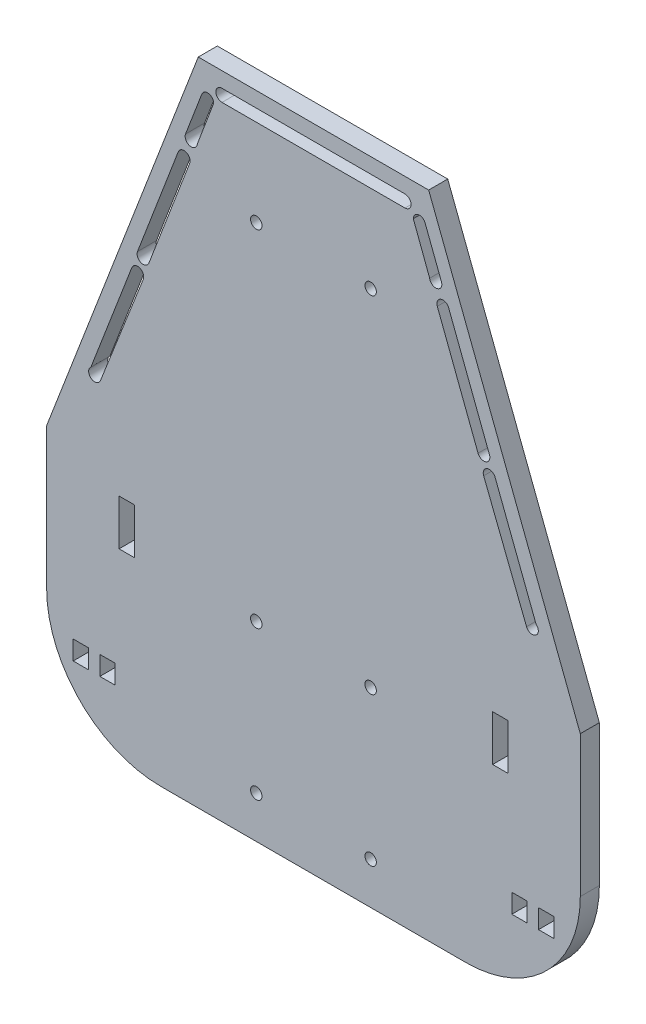
SolidWorks part; units mm, degrees
ref_plane "Front Plane" through (0, 0, 0) normal (0, 0, 1) x (1, 0, 0)
ref_plane "Top Plane" through (0, 0, 0) normal (0, 1, 0) x (1, 0, 0)
ref_plane "Right Plane" through (0, 0, 0) normal (1, 0, 0) x (0, 0, -1)
sketch "Sketch2" plane through (0, 0, 0) normal (0, 0, 1) x (1, 0, 0)
  line L0 (0, 0) -> (40, 0)
  line L1 (0, 0) -> (-40, 0)
  line L2 (-70, 30) -> (-70, 67)
  line L3 (70, 30) -> (70, 67)
  line L4 (-70, 67) -> (-30.2212, 170.6274)
  line L7 (70, 67) -> (30.2212, 170.6274)
  line L12 (-30.2212, 170.6274) -> (30.2212, 170.6274)
  arc A0 (-40, 0) -> (-70, 30) centre (-40, 30) cw
  arc A1 (40, 0) -> (70, 30) centre (40, 30) ccw
  dimension "D1" = 30
  dimension "D2" = 30
  dimension "D3" = 60.4423
  dimension "D5" = 37
  dimension "D6" = 70
  dimension "D7" = 70
  dimension "D8" = 159
  dimension "D9" = 159
  dimension "D10" = 111
  dimension "D11" = 111
  dimension "D12" = 37
extrude "Boss-Extrude2" add sketch "Sketch2" along normal blind 1
sketch "Sketch41" plane through (0, 0, 1) normal (0, 0, 1) x (1, 0, 0)
  line L0 (-33.5636, 151.4672) -> (-29.2832, 162.6778)
  line L1 (-32.4778, 145.3397) -> (-43.1788, 117.3131)
  line L2 (24, 166.6274) -> (-24, 166.6274)
  line L3 (-24, 163.4274) -> (24, 163.4274)
  line L4 (-26.1885, 162.1071) -> (-30.4778, 150.7272)
  line L9 (-35.4674, 146.4812) -> (-46.1683, 118.4546)
  line L10 (33.5636, 151.4672) -> (29.2832, 162.6778)
  line L11 (-55.8956, 84.2573) -> (-44.6465, 112.9189)
  line L12 (26.1885, 162.1071) -> (30.4778, 150.7272)
  line L13 (-47.6397, 114.0937) -> (-58.3908, 86.0863)
  line L14 (35.4674, 146.4812) -> (46.1683, 118.4546)
  line L15 (32.4778, 145.3397) -> (43.1788, 117.3131)
  line L16 (55.8956, 84.2573) -> (44.6465, 112.9189)
  line L17 (47.6397, 114.0937) -> (58.3908, 86.0863)
  line L18 (0, 0) -> (-11, 0)
  line L19 (51, 48.5) -> (47, 48.5)
  line L20 (-40, 0) -> (40, 0) construction
  line L21 (51, 60.5) -> (47, 60.5)
  line L22 (-63.037, 17) -> (-59.037, 17)
  line L23 (-63.037, 17) -> (-63.037, 22)
  line L24 (-63.037, 22) -> (-59.037, 22)
  line L25 (-59.037, 17) -> (-59.037, 22)
  line L26 (47, 48.5) -> (47, 60.5)
  line L27 (-56.037, 17) -> (-52.037, 17)
  line L28 (-56.037, 17) -> (-56.037, 22)
  line L29 (-56.037, 22) -> (-52.037, 22)
  line L30 (-52.037, 17) -> (-52.037, 22)
  line L31 (-51, 48.5) -> (-47, 48.5)
  line L32 (-51, 48.5) -> (-51, 60.5)
  line L33 (-51, 60.5) -> (-47, 60.5)
  line L34 (-47, 48.5) -> (-47, 60.5)
  line L35 (51, 48.5) -> (51, 60.5)
  line L36 (56.037, 17) -> (52.037, 17)
  line L37 (52.037, 17) -> (52.037, 22)
  line L38 (56.037, 17) -> (56.037, 22)
  line L39 (56.037, 22) -> (52.037, 22)
  line L40 (63.037, 17) -> (59.037, 17)
  line L41 (59.037, 17) -> (59.037, 22)
  line L42 (63.037, 22) -> (59.037, 22)
  line L43 (63.037, 17) -> (63.037, 22)
  arc A0 (-24, 166.6274) -> (-24, 163.4274) centre (-24, 165.0274) ccw
  arc A1 (24, 166.6274) -> (24, 163.4274) centre (24, 165.0274) cw
  arc A2 (-29.2832, 162.6778) -> (-26.1885, 162.1071) centre (-27.7885, 162.1071) cw
  arc A3 (-33.5636, 151.4672) -> (-30.4778, 150.7272) centre (-32.0689, 150.8964) ccw
  arc A4 (-35.4674, 146.4812) -> (-32.4778, 145.3397) centre (-33.9726, 145.9104) cw
  arc A5 (-43.1788, 117.3131) -> (-46.1683, 118.4546) centre (-44.6736, 117.8839) cw
  arc A6 (-44.6465, 112.9189) -> (-47.6397, 114.0937) centre (-46.1431, 113.5063) ccw
  arc A7 (-55.8956, 84.2573) -> (-58.3908, 86.0863) centre (-57.385, 84.8419) cw
  arc A8 (29.2832, 162.6778) -> (26.1885, 162.1071) centre (27.7885, 162.1071) ccw
  arc A9 (33.5636, 151.4672) -> (30.4778, 150.7272) centre (32.0689, 150.8964) cw
  arc A10 (35.4674, 146.4812) -> (32.4778, 145.3397) centre (33.9726, 145.9104) ccw
  arc A11 (43.1788, 117.3131) -> (46.1683, 118.4546) centre (44.6736, 117.8839) ccw
  arc A12 (44.6465, 112.9189) -> (47.6397, 114.0937) centre (46.1431, 113.5063) cw
  arc A13 (55.8956, 84.2573) -> (58.3908, 86.0863) centre (57.385, 84.8419) ccw
  circle A14 centre (-15, 140.6274) radius 1.5
  circle A15 centre (-15, 15) radius 1.5
  circle A16 centre (-15, 65) radius 1.5
  circle A17 centre (15, 140.6274) radius 1.5
  circle A18 centre (15, 65) radius 1.5
  circle A19 centre (15, 15) radius 1.5
  point P8 (0, 166.6274)
extrude "Cut-Extrude42" cut sketch "Sketch41" against normal blind 19 contours L38 L39 L37 L36 | L27 L30 L29 L28 | A16 | A18 | A7 L11 A6 L13 | A5 L1 A4 L9 | A1 L2 A0 L3 | A9 L10 A8 L12 | L16 A13 L17 A12 | A14 | A17 | L26 L21 L35 L19 | L32 L33 L34 L31 | L41 L42 L43 L40 | A19 | A15 | L24 L25 L22 L23 | L0 A2 L4 A3 | L14 A11 L15 A10
sketch "Sketch42" plane through (0, 0, 1) normal (0, 0, 1) x (1, 0, 0)
  line L6 (-40, 0) -> (40, 0)
  line L7 (70, 30) -> (70, 67)
  line L8 (70, 67) -> (30.2212, 170.6274)
  line L9 (30.2212, 170.6274) -> (-30.2212, 170.6274)
  line L10 (-30.2212, 170.6274) -> (-70, 67)
  line L11 (-70, 67) -> (-70, 30)
  line L12 (-40, 0) -> (40, 0)
  line L13 (70, 30) -> (70, 67)
  line L14 (70, 67) -> (30.2212, 170.6274)
  line L15 (30.2212, 170.6274) -> (-30.2212, 170.6274)
  line L16 (-30.2212, 170.6274) -> (-70, 67)
  line L17 (-70, 67) -> (-70, 30)
  arc A2 (40, 0) -> (70, 30) centre (40, 30) ccw
  arc A3 (-70, 30) -> (-40, 0) centre (-40, 30) ccw
  arc A4 (40, 0) -> (70, 30) centre (40, 30) ccw
  arc A5 (-70, 30) -> (-40, 0) centre (-40, 30) ccw
  dimension "D1" = 0
extrude "Boss-Extrude17" add sketch "Sketch42" along normal blind 4
sketch "Sketch45" plane through (0, 0, 5) normal (0, 0, 1) x (1, 0, 0)
sketch "Sketch47" plane through (0, 0, 0) normal (0, 0, -1) x (-1, 0, 0)
  line L0 (63.037, 17) -> (63.037, 22) construction
  line L1 (63.037, 22) -> (59.037, 22) construction
  line L2 (59.037, 22) -> (59.037, 17) construction
  line L3 (59.037, 17) -> (63.037, 17) construction
  line L4 (52.037, 22) -> (52.037, 17) construction
  line L5 (52.037, 17) -> (56.037, 17) construction
  line L6 (56.037, 17) -> (56.037, 22) construction
  line L7 (56.037, 22) -> (52.037, 22) construction
  line L8 (-52.037, 22) -> (-56.037, 22) construction
  line L9 (-56.037, 22) -> (-56.037, 17) construction
  line L10 (-56.037, 17) -> (-52.037, 17) construction
  line L11 (-52.037, 17) -> (-52.037, 22) construction
  line L12 (-63.037, 17) -> (-59.037, 17) construction
  line L13 (-59.037, 17) -> (-59.037, 22) construction
  line L14 (-59.037, 22) -> (-63.037, 22) construction
  line L15 (-63.037, 22) -> (-63.037, 17) construction
  line L16 (-51, 48.5) -> (-47, 48.5) construction
  line L17 (-47, 48.5) -> (-47, 60.5) construction
  line L18 (-47, 60.5) -> (-51, 60.5) construction
  line L19 (-51, 60.5) -> (-51, 48.5) construction
  line L20 (47, 60.5) -> (47, 48.5) construction
  line L21 (47, 48.5) -> (51, 48.5) construction
  line L22 (51, 48.5) -> (51, 60.5) construction
  line L23 (51, 60.5) -> (47, 60.5) construction
  line L24 (63.037, 17) -> (63.037, 22)
  line L25 (63.037, 22) -> (59.037, 22)
  line L26 (59.037, 22) -> (59.037, 17)
  line L27 (59.037, 17) -> (63.037, 17)
  line L28 (52.037, 22) -> (52.037, 17)
  line L29 (52.037, 17) -> (56.037, 17)
  line L30 (56.037, 17) -> (56.037, 22)
  line L31 (56.037, 22) -> (52.037, 22)
  line L32 (-52.037, 22) -> (-56.037, 22)
  line L33 (-56.037, 22) -> (-56.037, 17)
  line L34 (-56.037, 17) -> (-52.037, 17)
  line L35 (-52.037, 17) -> (-52.037, 22)
  line L36 (-63.037, 17) -> (-59.037, 17)
  line L37 (-59.037, 17) -> (-59.037, 22)
  line L38 (-59.037, 22) -> (-63.037, 22)
  line L39 (-63.037, 22) -> (-63.037, 17)
  line L40 (-51, 48.5) -> (-47, 48.5)
  line L41 (-47, 48.5) -> (-47, 60.5)
  line L42 (-47, 60.5) -> (-51, 60.5)
  line L43 (-51, 60.5) -> (-51, 48.5)
  line L44 (47, 60.5) -> (47, 48.5)
  line L45 (47, 48.5) -> (51, 48.5)
  line L46 (51, 48.5) -> (51, 60.5)
  line L47 (51, 60.5) -> (47, 60.5)
extrude "Cut-Extrude47" cut sketch "Sketch47" against normal through all
sketch "Sketch48" plane through (0, 0, 0) normal (0, 0, -1) x (-1, 0, 0)
  line L0 (-43.1788, 117.3131) -> (-32.4778, 145.3397) construction
  line L1 (-35.4674, 146.4812) -> (-46.1683, 118.4546) construction
  line L2 (-55.8956, 84.2573) -> (-44.6465, 112.9189) construction
  line L3 (-47.6397, 114.0937) -> (-58.3908, 86.0863) construction
  line L4 (-30.4778, 150.7272) -> (-26.1885, 162.1071) construction
  line L5 (-29.2832, 162.6778) -> (-33.5636, 151.4672) construction
  line L6 (-24, 163.4274) -> (24, 163.4274) construction
  line L7 (24, 166.6274) -> (-24, 166.6274) construction
  line L8 (26.1885, 162.1071) -> (30.4778, 150.7272) construction
  line L9 (33.5636, 151.4672) -> (29.2832, 162.6778) construction
  line L10 (46.1683, 118.4546) -> (35.4674, 146.4812) construction
  line L11 (32.4778, 145.3397) -> (43.1788, 117.3131) construction
  line L12 (58.3908, 86.0863) -> (47.6397, 114.0937) construction
  line L13 (44.6465, 112.9189) -> (55.8956, 84.2573) construction
  line L14 (-43.1788, 117.3131) -> (-32.4778, 145.3397)
  line L15 (-35.4674, 146.4812) -> (-46.1683, 118.4546)
  line L16 (-55.8956, 84.2573) -> (-44.6465, 112.9189)
  line L17 (-47.6397, 114.0937) -> (-58.3908, 86.0863)
  line L18 (-30.4778, 150.7272) -> (-26.1885, 162.1071)
  line L19 (-29.2832, 162.6778) -> (-33.5636, 151.4672)
  line L20 (-24, 163.4274) -> (24, 163.4274)
  line L21 (24, 166.6274) -> (-24, 166.6274)
  line L22 (26.1885, 162.1071) -> (30.4778, 150.7272)
  line L23 (33.5636, 151.4672) -> (29.2832, 162.6778)
  line L24 (46.1683, 118.4546) -> (35.4674, 146.4812)
  line L25 (32.4778, 145.3397) -> (43.1788, 117.3131)
  line L26 (58.3908, 86.0863) -> (47.6397, 114.0937)
  line L27 (44.6465, 112.9189) -> (55.8956, 84.2573)
  arc A0 (-32.4778, 145.3397) -> (-35.4674, 146.4812) centre (-33.9726, 145.9104) ccw construction
  arc A1 (-46.1683, 118.4546) -> (-43.1788, 117.3131) centre (-44.6736, 117.8839) ccw construction
  arc A2 (-44.6465, 112.9189) -> (-47.6397, 114.0937) centre (-46.1431, 113.5063) ccw construction
  arc A3 (-58.3908, 86.0863) -> (-55.8956, 84.2573) centre (-57.385, 84.8419) ccw construction
  arc A4 (-33.5636, 151.4672) -> (-30.4778, 150.7272) centre (-32.0689, 150.8964) ccw construction
  arc A5 (-26.1885, 162.1071) -> (-29.2832, 162.6778) centre (-27.7885, 162.1071) ccw construction
  arc A6 (-24, 166.6274) -> (-24, 163.4274) centre (-24, 165.0274) ccw construction
  arc A7 (24, 163.4274) -> (24, 166.6274) centre (24, 165.0274) ccw construction
  circle A8 centre (-15, 140.6274) radius 1.5 construction
  circle A9 centre (15, 140.6274) radius 1.5 construction
  arc A10 (30.4778, 150.7272) -> (33.5636, 151.4672) centre (32.0689, 150.8964) ccw construction
  arc A11 (29.2832, 162.6778) -> (26.1885, 162.1071) centre (27.7885, 162.1071) ccw construction
  arc A12 (43.1788, 117.3131) -> (46.1683, 118.4546) centre (44.6736, 117.8839) ccw construction
  arc A13 (35.4674, 146.4812) -> (32.4778, 145.3397) centre (33.9726, 145.9104) ccw construction
  arc A14 (55.8956, 84.2573) -> (58.3908, 86.0863) centre (57.385, 84.8419) ccw construction
  arc A15 (47.6397, 114.0937) -> (44.6465, 112.9189) centre (46.1431, 113.5063) ccw construction
  arc A16 (-32.4778, 145.3397) -> (-35.4674, 146.4812) centre (-33.9726, 145.9104) ccw
  arc A17 (-46.1683, 118.4546) -> (-43.1788, 117.3131) centre (-44.6736, 117.8839) ccw
  arc A18 (-44.6465, 112.9189) -> (-47.6397, 114.0937) centre (-46.1431, 113.5063) ccw
  arc A19 (-58.3908, 86.0863) -> (-55.8956, 84.2573) centre (-57.385, 84.8419) ccw
  arc A20 (-33.5636, 151.4672) -> (-30.4778, 150.7272) centre (-32.0689, 150.8964) ccw
  arc A21 (-26.1885, 162.1071) -> (-29.2832, 162.6778) centre (-27.7885, 162.1071) ccw
  arc A22 (-24, 166.6274) -> (-24, 163.4274) centre (-24, 165.0274) ccw
  arc A23 (24, 163.4274) -> (24, 166.6274) centre (24, 165.0274) ccw
  circle A24 centre (-15, 140.6274) radius 1.5
  circle A25 centre (15, 140.6274) radius 1.5
  arc A26 (30.4778, 150.7272) -> (33.5636, 151.4672) centre (32.0689, 150.8964) ccw
  arc A27 (29.2832, 162.6778) -> (26.1885, 162.1071) centre (27.7885, 162.1071) ccw
  arc A28 (43.1788, 117.3131) -> (46.1683, 118.4546) centre (44.6736, 117.8839) ccw
  arc A29 (35.4674, 146.4812) -> (32.4778, 145.3397) centre (33.9726, 145.9104) ccw
  arc A30 (55.8956, 84.2573) -> (58.3908, 86.0863) centre (57.385, 84.8419) ccw
  arc A31 (47.6397, 114.0937) -> (44.6465, 112.9189) centre (46.1431, 113.5063) ccw
extrude "Cut-Extrude44" cut sketch "Sketch48" against normal through all
sketch "Sketch51" plane through (0, 0, 0) normal (0, 0, -1) x (-1, 0, 0)
  circle A0 centre (-15, 65) radius 1.5 construction
  circle A1 centre (-15, 65) radius 1.5
extrude "Boss-Extrude18" add sketch "Sketch51" against normal blind 1
sketch "Sketch52" plane through (0, 0, 0) normal (0, 0, -1) x (-1, 0, 0)
  circle A0 centre (15, 65) radius 1.5 construction
  circle A1 centre (15, 65) radius 1.5
extrude "Boss-Extrude19" add sketch "Sketch52" against normal blind 2
sketch "Sketch53" plane through (0, 0, 5) normal (0, 0, 1) x (1, 0, 0)
  line L0 (-40, 0) -> (40, 0) construction
  circle A1 centre (-15, 50) radius 1.5
  circle A2 centre (15, 50) radius 1.5
  dimension "D1" = 3
  dimension "D2" = 3
  dimension "D3" = 50
  dimension "D4" = 50
extrude "Cut-Extrude46" cut sketch "Sketch53" against normal through all
sketch "Sketch54" plane through (0, 0, 5) normal (0, 0, 1) x (1, 0, 0)
sketch "Sketch55" plane through (0, 0, 0) normal (0, 0, -1) x (-1, 0, 0)
  circle A1 centre (-15, 15) radius 1.5
  circle A2 centre (-15, 15) radius 1.5
  circle A3 centre (15, 15) radius 1.5
  circle A4 centre (15, 15) radius 1.5
  dimension "D1" = 0
  dimension "D2" = 0
extrude "Boss-Extrude20" add sketch "Sketch55" against normal blind 1
sketch "Sketch58" plane through (0, 0, 0) normal (0, 0, -1) x (-1, 0, 0)
  line L0 (0, 0) -> (-15, 0)
  line L1 (40, 0) -> (-40, 0) construction
  line L2 (0, 0) -> (15, 0)
  circle A0 centre (-15, 11) radius 1.5
  circle A1 centre (15, 11) radius 1.5
  dimension "D1" = 3
  dimension "D2" = 3
extrude "Cut-Extrude45" cut sketch "Sketch58" against normal through all contours A0 | A1
sketch "Sketch59" plane through (0, 0, 0) normal (0, 0, -1) x (-1, 0, 0)
